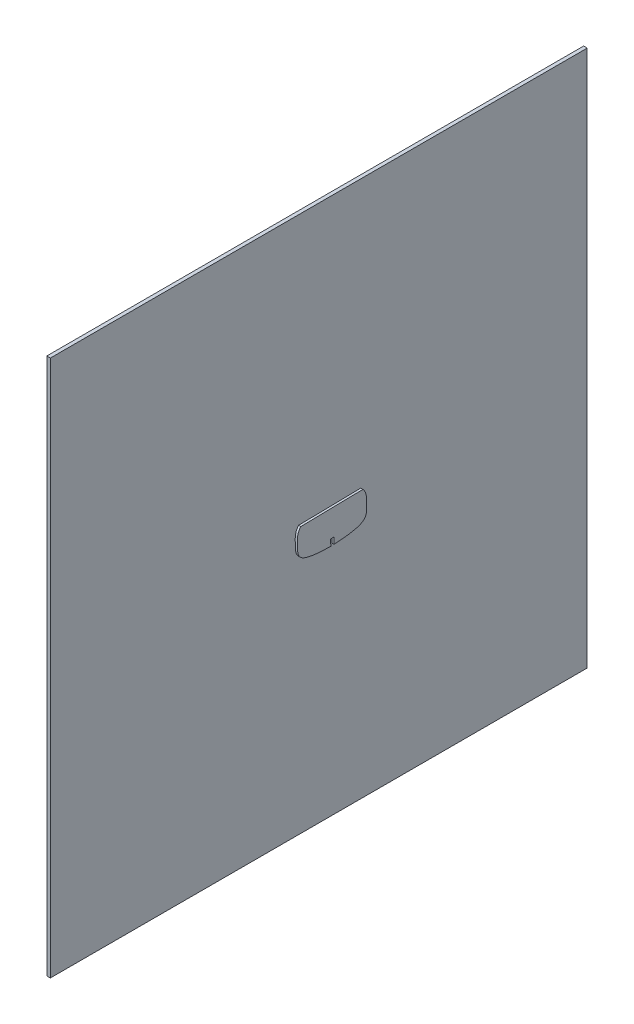
SolidWorks part; units mm, degrees
ref_plane "Plan de face" through (0, 0, 0) normal (0, 0, 1) x (1, 0, 0)
ref_plane "Plan de dessus" through (0, 0, 0) normal (0, 1, 0) x (1, 0, 0)
ref_plane "Plan de droite" through (0, 0, 0) normal (1, 0, 0) x (0, 0, -1)
sketch "Esquisse1" plane through (0, 0, 0) normal (0, 0, 1) x (1, 0, 0)
  point P0 (-20, 0)
  dimension "D1" = 20
sketch3d "Esquisse3D1"
  line L1 (-20, 1121.2893, 777.275) -> (-20, 1121.2893, -722.725)
  line L2 (-20, 1121.2893, 777.275) -> (-20, -378.7107, 777.275)
  line L3 (-20, -378.7107, 777.275) -> (-20, -378.7107, -722.725)
  line L4 (-20, 1121.2893, -722.725) -> (-20, -378.7107, -722.725)
  dimension "D1" = 1500
  dimension "D2" = 1500
extrude "Boss.-Extru.2" add sketch "Esquisse3D1" along direction (1, 0, 0) on the side of the normal blind 10 contours L2 L1 L4 L3
sketch "Esquisse4" plane through (-10, 0, 0) normal (1, 0, 0) x (0, 0, -1)
  line L0 (0, 0) -> (-7.701, 425.1082) construction
  line L1 (169.3944, 339.9131) -> (-188.5193, 333.4294) construction
  line L2 (-187.2006, 249.23) -> (169.0622, 255.6839) construction
  line L3 (-144.268, 175.2448) -> (126.4811, 180.1495) construction
sketch "Esquisse5" plane through (0, 0, 0) normal (1, 0, 0) x (0, 0, -1)
  line L0 (-7.701, 425.1082) -> (0, 0) construction
  line L2 (-93.7553, 379.7777) -> (-120.8635, 346.9838) construction
  line L3 (-120.8635, 346.9838) -> (-72.6155, 325.8977) construction
  line L5 (-72.6155, 325.8977) -> (-154.101, 291.588) construction
  line L7 (-154.101, 291.588) -> (-5.2533, 289.9921) construction
  line L18 (-93.7553, 379.7777) -> (79.9387, 382.9243)
  line L19 (79.9387, 382.9243) -> (108.2168, 351.1337) construction
  line L20 (108.2168, 351.1337) -> (60.7643, 328.3139) construction
  line L21 (60.7643, 328.3139) -> (143.4389, 296.9781) construction
  line L28 (143.4389, 296.9781) -> (-5.2533, 289.9921) construction
  spline S0 degree 4 poles (-93.7553, 379.7777) (-120.8635, 346.9838) (-72.6155, 325.8977) (-154.101, 291.588) (-5.2533, 289.9921) knots 0 0 0 0 0 1 1 1 1 1
  spline S1 degree 4 poles (79.9387, 382.9243) (108.2168, 351.1337) (60.7643, 328.3139) (143.4389, 296.9781) (-5.2533, 289.9921) knots 0 0 0 0 0 1 1 1 1 1
  point P14 (-6.9083, 381.351)
extrude "Boss.-Extru.3" add sketch "Esquisse5" along normal blind 6 separate body
sketch "Esquisse6" plane through (6, 0, 0) normal (1, 0, 0) x (0, 0, -1)
  line L0 (-9.7559, 290.0528) -> (-10.082, 308.0528)
  line L1 (-10.082, 308.0528) -> (-1.082, 308.2158)
  line L2 (-1.082, 308.2158) -> (-0.7559, 290.2158)
  line L3 (-187.2006, 249.23) -> (169.0622, 255.6839) construction
  line L4 (0, 0) -> (-7.701, 425.1082) construction
  line L5 (-9.7559, 290.0528) -> (-0.7559, 290.2158) construction
  line L6 (-9.7559, 290.0528) -> (-13.542, 279.2036)
  line L7 (-13.542, 279.2036) -> (9.7983, 280.7094)
  line L8 (9.7983, 280.7094) -> (-0.7559, 290.2158)
  spline S0 degree 4 poles (-93.7553, 379.7777) (-120.8635, 346.9838) (-72.6155, 325.8977) (-154.101, 291.588) (-5.2533, 289.9921) knots 0 0 0 0 0 1 1 1 1 1 construction
  spline S1 degree 4 poles (-5.2533, 289.9921) (143.4389, 296.9781) (60.7643, 328.3139) (108.2168, 351.1337) (79.9387, 382.9243) knots 0 0 0 0 0 1 1 1 1 1 construction
  dimension "D1" = 9
  dimension "D2" = 18
extrude "Enlèv. mat.-Extru.1" cut sketch "Esquisse6" against normal blind 10
